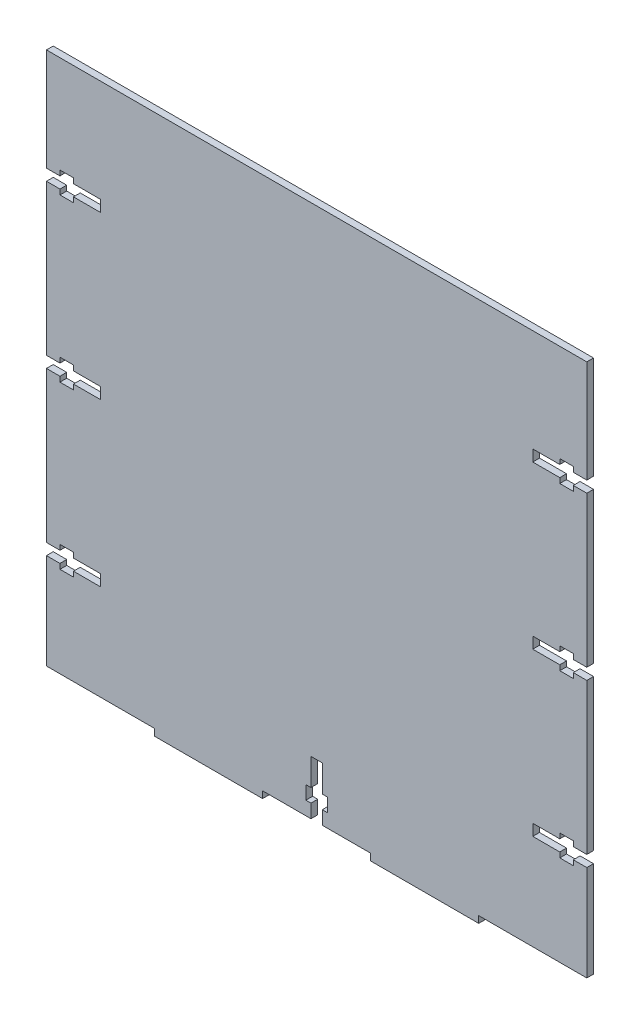
SolidWorks part; units mm, degrees
material "Oak"
ref_plane "Front Plane" through (0, 0, 0) normal (0, 0, 1) x (1, 0, 0)
ref_plane "Top Plane" through (0, 0, 0) normal (0, 1, 0) x (1, 0, 0)
ref_plane "Right Plane" through (0, 0, 0) normal (1, 0, 0) x (0, 0, -1)
sketch "Sketch1" plane through (0, 0, 0) normal (0, 0, 1) x (1, 0, 0)
  line L0 (-20, -100) -> (-20, -97.5)
  line L1 (-100, 100) -> (100, 100)
  line L2 (-100, 100) -> (-100, -100)
  line L3 (-100, -100) -> (100, -100)
  line L4 (100, 100) -> (100, -100)
  line L5 (-100, 100) -> (100, -100) construction
  line L6 (-100, -100) -> (100, 100) construction
  line L7 (-100, -100) -> (-60, -100)
  line L8 (-100, -100) -> (-100, -97.5)
  line L9 (-100, -97.5) -> (-60, -97.5)
  line L10 (-60, -100) -> (-60, -97.5)
  line L11 (-20, -100) -> (20, -100)
  line L12 (20, -100) -> (20, -97.5)
  line L13 (-20, -97.5) -> (20, -97.5)
  line L14 (60, -100) -> (60, -97.5)
  line L15 (60, -100) -> (100, -100)
  line L16 (100, -100) -> (100, -97.5)
  line L17 (60, -97.5) -> (100, -97.5)
  line L18 (0, -109.7122) -> (0, -77.5)
  line L20 (-2.1, -97.5) -> (2.1, -97.5)
  line L21 (-2.1, -97.5) -> (-2.1, -77.5)
  line L22 (-2.1, -77.5) -> (2.1, -77.5)
  line L23 (2.1, -97.5) -> (2.1, -77.5)
  line L24 (-4, -87.5) -> (4, -87.5)
  line L25 (-4, -87.5) -> (-4, -92.5)
  line L26 (-4, -92.5) -> (4, -92.5)
  line L27 (4, -87.5) -> (4, -92.5)
  line L28 (-4, -87.5) -> (4, -92.5) construction
  line L29 (-4, -92.5) -> (4, -87.5) construction
  point P0 (0, 0)
  point P23 (0, -90)
  dimension "D1" = 200
  dimension "D2" = 200
  dimension "D3" = 40
  dimension "D4" = 2.5
  dimension "D6" = 20
  dimension "D7" = 4.2
  dimension "D8" = 8
  dimension "D9" = 5
  dimension "D10" = 5
  dimension "D5" = 3
extrude "Boss-Extrude1" add sketch "Sketch1" along normal blind 2.5 contours L24 L27 L26 L23 L13 L12 L3 L14 L17 L4 L1 L2 L9 L10 L0 L21 L25 L22
sketch "Sketch4" plane through (0, 0, 0) normal (0, 0, -1) x (-1, 0, 0)
  line L0 (-100, 62.1) -> (-100, 57.9)
  line L1 (-100, 2.1) -> (-95, 2.1)
  line L2 (-100, 2.1) -> (-100, -2.1)
  line L3 (-100, -2.1) -> (-95, -2.1)
  line L4 (-80, 2.1) -> (-80, -2.1)
  line L5 (-95, -2.1) -> (-95, -4)
  line L6 (-90, 4) -> (-95, 4)
  line L7 (-90, 4) -> (-90, 2.1)
  line L8 (-90, -4) -> (-95, -4)
  line L9 (-95, 4) -> (-95, 2.1)
  line L10 (-90, -2.1) -> (-80, -2.1)
  line L12 (0, 0) -> (-100, 0) construction
  line L13 (-100, 57.9) -> (-95, 57.9)
  line L14 (-90, 2.1) -> (-80, 2.1)
  line L17 (-90, -2.1) -> (-90, -4)
  line L18 (-100, 100) -> (-100, -97.5) construction
  line L40 (0, 0) -> (0, -31.4249)
  line L41 (-95, 57.9) -> (-95, 56)
  line L42 (-90, 56) -> (-95, 56)
  line L43 (-90, 57.9) -> (-90, 56)
  line L44 (-90, 57.9) -> (-80, 57.9)
  line L45 (-80, 62.1) -> (-80, 57.9)
  line L46 (-90, 62.1) -> (-80, 62.1)
  line L47 (-90, 64) -> (-90, 62.1)
  line L48 (-90, 64) -> (-95, 64)
  line L49 (-95, 64) -> (-95, 62.1)
  line L50 (-100, 62.1) -> (-95, 62.1)
  line L51 (-100, -57.9) -> (-100, -62.1)
  line L52 (-100, -62.1) -> (-95, -62.1)
  line L53 (-95, -62.1) -> (-95, -64)
  line L54 (-90, -64) -> (-95, -64)
  line L55 (-90, -62.1) -> (-90, -64)
  line L56 (-90, -62.1) -> (-80, -62.1)
  line L57 (-80, -57.9) -> (-80, -62.1)
  line L58 (-90, -57.9) -> (-80, -57.9)
  line L59 (-90, -56) -> (-90, -57.9)
  line L60 (-90, -56) -> (-95, -56)
  line L61 (-95, -56) -> (-95, -57.9)
  line L62 (-100, -57.9) -> (-95, -57.9)
  line L63 (100, -57.9) -> (95, -57.9)
  line L64 (95, -56) -> (95, -57.9)
  line L65 (90, -56) -> (95, -56)
  line L66 (90, -56) -> (90, -57.9)
  line L67 (90, -57.9) -> (80, -57.9)
  line L68 (80, -57.9) -> (80, -62.1)
  line L69 (90, -62.1) -> (80, -62.1)
  line L70 (90, -62.1) -> (90, -64)
  line L71 (90, -64) -> (95, -64)
  line L72 (95, -62.1) -> (95, -64)
  line L73 (100, -62.1) -> (95, -62.1)
  line L74 (100, -57.9) -> (100, -62.1)
  line L75 (100, 2.1) -> (95, 2.1)
  line L76 (95, 4) -> (95, 2.1)
  line L77 (90, 4) -> (95, 4)
  line L78 (90, 4) -> (90, 2.1)
  line L79 (90, 2.1) -> (80, 2.1)
  line L80 (80, 2.1) -> (80, -2.1)
  line L81 (90, -2.1) -> (80, -2.1)
  line L82 (90, -2.1) -> (90, -4)
  line L83 (90, -4) -> (95, -4)
  line L84 (95, -2.1) -> (95, -4)
  line L85 (100, -2.1) -> (95, -2.1)
  line L86 (100, 2.1) -> (100, -2.1)
  line L87 (100, 62.1) -> (95, 62.1)
  line L88 (95, 64) -> (95, 62.1)
  line L89 (90, 64) -> (95, 64)
  line L90 (90, 64) -> (90, 62.1)
  line L91 (90, 62.1) -> (80, 62.1)
  line L92 (80, 62.1) -> (80, 57.9)
  line L93 (90, 57.9) -> (80, 57.9)
  line L94 (90, 57.9) -> (90, 56)
  line L95 (90, 56) -> (95, 56)
  line L96 (95, 57.9) -> (95, 56)
  line L97 (100, 57.9) -> (95, 57.9)
  line L98 (100, 62.1) -> (100, 57.9)
  point P6 (-92.6261, 1.25)
  line M76 (100, -97.5) -> (100, 100)
  line M78 (-100, 100) -> (-100, -97.5)
  dimension "D1" = 4.2
  dimension "D2" = 20
  dimension "D3" = 5
  dimension "D4" = 8
  dimension "D5" = 5
  dimension "D6" = 2
  dimension "D7" = 2
  dimension "D8" = 1.9
  dimension "D9" = 1.9
extrude "Cut-Extrude1" cut sketch "Sketch4" against normal blind 2.5 contours L4 L12 L2 L3 L5 L8 L17 L10 | L12 L4 L14 L7 L6 L9 L1 M78 | L50 L13 L41 L42 L43 L44 L45 L46 L47 L48 L49 M78 | L62 L52 L53 L54 L55 L56 L57 L58 L59 L60 L61 M78 | L97 L87 L88 L89 L90 L91 L92 L93 L94 L95 L96 M76 | L85 L75 L76 L77 L78 L79 L80 L81 L82 L83 L84 M76 | L73 L63 L64 L65 L66 L67 L68 L69 L70 L71 L72 M76
